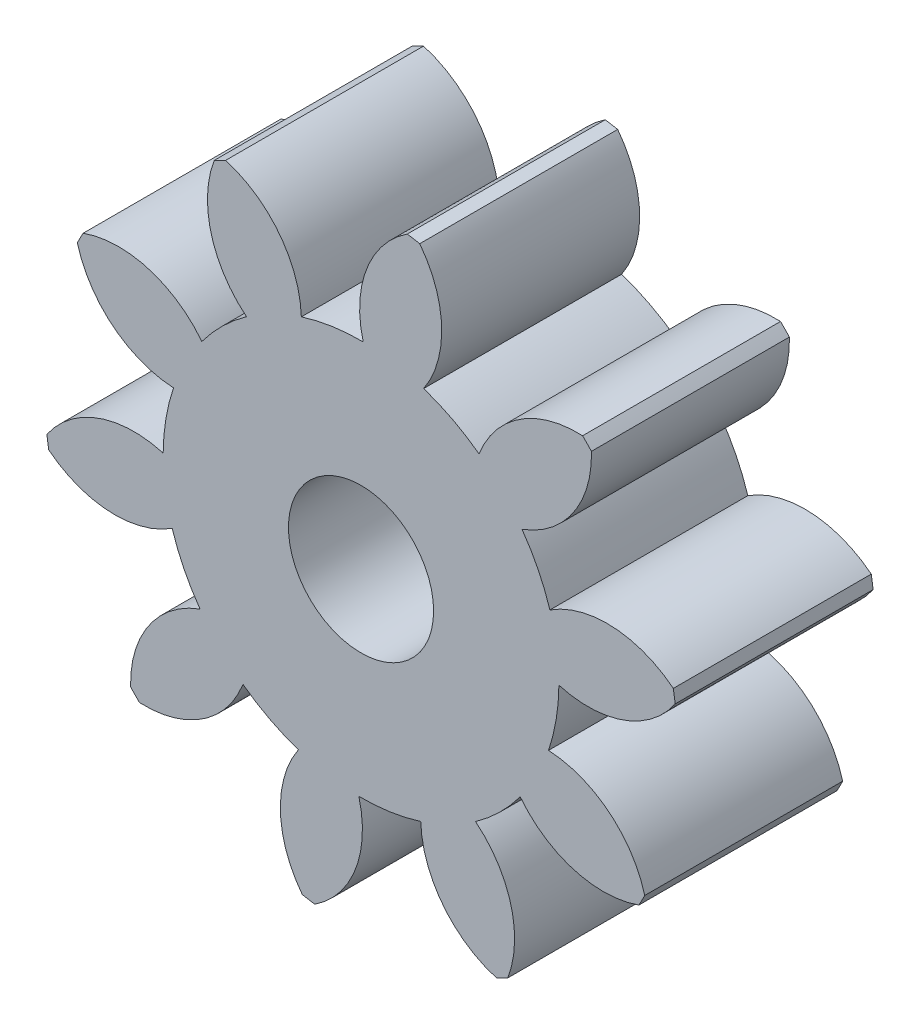
SolidWorks part; units mm, degrees
ref_plane "Front" through (0, 0, 0) normal (0, 0, 1) x (1, 0, 0)
ref_plane "Top" through (0, 0, 0) normal (0, 1, 0) x (1, 0, 0)
ref_plane "Right" through (0, 0, 0) normal (1, 0, 0) x (0, 0, -1)
sketch "Sketch1" plane through (0, 0, 0) normal (0, 0, 1) x (1, 0, 0)
  circle A0 centre (0, 0) radius 1.1
  circle A1 centre (0, 0) radius 6
  dimension "D1" = 2.2
  dimension "D2" = 12
extrude "Boss-Extrude1" add sketch "Sketch1" along normal mid plane 5.8
sketch "Sketch2" plane through (0, 0, 2.9) normal (0, 0, 1) x (1, 0, 0)
  circle A0 centre (0, 0) radius 6 construction
  circle A1 centre (0, 0) radius 6
  arc A82 (-0.9043, 2.8594) -> (-2.0525, 4.339) centre (-2.5033, 2.8039) ccw
  arc A83 (-2.0525, 4.339) -> (-2.2243, 4.2535) centre (0, 0) ccw
  arc A84 (-2.2243, 4.2535) -> (-1.7361, 2.4454) centre (-0.7277, 3.6877) ccw
  arc A85 (-1.7361, 2.4454) -> (-2.4123, 1.7818) centre (0, 0) ccw
  arc A86 (-2.4123, 1.7818) -> (-4.2109, 2.3039) centre (-3.6733, 0.7969) ccw
  arc A87 (-4.2109, 2.3039) -> (-4.2997, 2.1337) centre (0, 0) ccw
  arc A88 (-4.2997, 2.1337) -> (-2.8419, 0.9579) centre (-2.7563, 2.5556) ccw
  arc A89 (-2.8419, 0.9579) -> (-2.9989, 0.0236) centre (0, 0) ccw
  arc A90 (-2.9989, 0.0236) -> (-4.7609, -0.6112) centre (-3.4402, -1.5144) ccw
  arc A91 (-4.7609, -0.6112) -> (-4.7327, -0.801) centre (0, 0) ccw
  arc A92 (-4.7327, -0.801) -> (-2.8622, -0.8955) centre (-3.732, 0.4474) ccw
  arc A93 (-2.8622, -0.8955) -> (-2.44, -1.7437) centre (0, 0) ccw
  arc A94 (-2.44, -1.7437) -> (-3.4924, -3.2929) centre (-1.8931, -3.2473) ccw
  arc A95 (-3.4924, -3.2929) -> (-3.358, -3.4299) centre (0, 0) ccw
  arc A96 (-3.358, -3.4299) -> (-1.7892, -2.4068) centre (-3.2823, -1.8317) ccw
  arc A97 (-1.7892, -2.4068) -> (-0.9491, -2.8448) centre (0, 0) ccw
  arc A98 (-0.9491, -2.8448) -> (-0.8899, -4.7168) centre (0.3772, -3.7398) ccw
  arc A99 (-0.8899, -4.7168) -> (-0.7006, -4.7486) centre (0, 0) ccw
  arc A100 (-0.7006, -4.7486) -> (-0.0328, -2.9988) centre (-1.5788, -3.4111) ccw
  arc A101 (-0.0328, -2.9988) -> (0.9043, -2.8594) centre (0, 0) ccw
  arc A102 (0.9043, -2.8594) -> (2.0525, -4.339) centre (2.5033, -2.8039) ccw
  arc A103 (2.0525, -4.339) -> (2.2243, -4.2535) centre (0, 0) ccw
  arc A104 (2.2243, -4.2535) -> (1.7361, -2.4454) centre (0.7277, -3.6877) ccw
  arc A105 (1.7361, -2.4454) -> (2.4123, -1.7818) centre (0, 0) ccw
  arc A106 (2.4123, -1.7818) -> (4.2109, -2.3039) centre (3.6733, -0.7969) ccw
  arc A107 (4.2109, -2.3039) -> (4.2997, -2.1337) centre (0, 0) ccw
  arc A108 (4.2997, -2.1337) -> (2.8419, -0.9579) centre (2.7563, -2.5556) ccw
  arc A109 (2.8419, -0.9579) -> (2.9989, -0.0236) centre (0, 0) ccw
  arc A110 (2.9989, -0.0236) -> (4.7609, 0.6112) centre (3.4402, 1.5144) ccw
  arc A111 (4.7609, 0.6112) -> (4.7327, 0.801) centre (0, 0) ccw
  arc A112 (4.7327, 0.801) -> (2.8622, 0.8955) centre (3.732, -0.4474) ccw
  arc A113 (2.8622, 0.8955) -> (2.44, 1.7437) centre (0, 0) ccw
  arc A114 (2.44, 1.7437) -> (3.4924, 3.2929) centre (1.8931, 3.2473) ccw
  arc A115 (3.4924, 3.2929) -> (3.358, 3.4299) centre (0, 0) ccw
  arc A116 (3.358, 3.4299) -> (1.7892, 2.4068) centre (3.2823, 1.8317) ccw
  arc A117 (1.7892, 2.4068) -> (0.9491, 2.8448) centre (0, 0) ccw
  arc A118 (0.9491, 2.8448) -> (0.8899, 4.7168) centre (-0.3772, 3.7398) ccw
  arc A119 (0.8899, 4.7168) -> (0.7006, 4.7486) centre (0, 0) ccw
  arc A120 (0.7006, 4.7486) -> (0.0328, 2.9988) centre (1.5788, 3.4111) ccw
  arc A121 (0.0328, 2.9988) -> (-0.9043, 2.8594) centre (0, 0) ccw
extrude "Cut-Extrude1" cut sketch "Sketch2" against normal through all
sketch "Sketch3" plane through (0, 0, 2.9) normal (0, 0, 1) x (1, 0, 0)
  arc A40 (0.7006, 4.7486) -> (0.0328, 2.9988) centre (1.5788, 3.4111) ccw
  arc A41 (0.0328, 2.9988) -> (-0.9043, 2.8594) centre (0, 0) ccw
  arc A42 (-0.9043, 2.8594) -> (-2.0525, 4.339) centre (-2.5033, 2.8039) ccw
  arc A43 (-2.0525, 4.339) -> (-2.2243, 4.2535) centre (0, 0) ccw
  arc A44 (-2.2243, 4.2535) -> (-1.7361, 2.4454) centre (-0.7277, 3.6877) ccw
  arc A45 (-1.7361, 2.4454) -> (-2.4123, 1.7818) centre (0, 0) ccw
  arc A46 (-2.4123, 1.7818) -> (-4.2109, 2.3039) centre (-3.6733, 0.7969) ccw
  arc A47 (-4.2109, 2.3039) -> (-4.2997, 2.1337) centre (0, 0) ccw
  arc A48 (-4.2997, 2.1337) -> (-2.8419, 0.9579) centre (-2.7563, 2.5556) ccw
  arc A49 (-2.8419, 0.9579) -> (-2.9989, 0.0236) centre (0, 0) ccw
  arc A50 (-2.9989, 0.0236) -> (-4.7609, -0.6112) centre (-3.4402, -1.5144) ccw
  arc A51 (-4.7609, -0.6112) -> (-4.7327, -0.801) centre (0, 0) ccw
  arc A52 (-4.7327, -0.801) -> (-2.8622, -0.8955) centre (-3.732, 0.4474) ccw
  arc A53 (-2.8622, -0.8955) -> (-2.44, -1.7437) centre (0, 0) ccw
  arc A54 (-2.44, -1.7437) -> (-3.4924, -3.2929) centre (-1.8931, -3.2473) ccw
  arc A55 (-3.4924, -3.2929) -> (-3.358, -3.4299) centre (0, 0) ccw
  arc A56 (-3.358, -3.4299) -> (-1.7892, -2.4068) centre (-3.2823, -1.8317) ccw
  arc A57 (-1.7892, -2.4068) -> (-0.9491, -2.8448) centre (0, 0) ccw
  arc A58 (-0.9491, -2.8448) -> (-0.8899, -4.7168) centre (0.3772, -3.7398) ccw
  arc A59 (-0.8899, -4.7168) -> (-0.7006, -4.7486) centre (0, 0) ccw
  arc A60 (-0.7006, -4.7486) -> (-0.0328, -2.9988) centre (-1.5788, -3.4111) ccw
  arc A61 (-0.0328, -2.9988) -> (0.9043, -2.8594) centre (0, 0) ccw
  arc A62 (0.9043, -2.8594) -> (2.0525, -4.339) centre (2.5033, -2.8039) ccw
  arc A63 (2.0525, -4.339) -> (2.2243, -4.2535) centre (0, 0) ccw
  arc A64 (2.2243, -4.2535) -> (1.7361, -2.4454) centre (0.7277, -3.6877) ccw
  arc A65 (1.7361, -2.4454) -> (2.4123, -1.7818) centre (0, 0) ccw
  arc A66 (2.4123, -1.7818) -> (4.2109, -2.3039) centre (3.6733, -0.7969) ccw
  arc A67 (4.2109, -2.3039) -> (4.2997, -2.1337) centre (0, 0) ccw
  arc A68 (4.2997, -2.1337) -> (2.8419, -0.9579) centre (2.7563, -2.5556) ccw
  arc A69 (2.8419, -0.9579) -> (2.9989, -0.0236) centre (0, 0) ccw
  arc A70 (2.9989, -0.0236) -> (4.7609, 0.6112) centre (3.4402, 1.5144) ccw
  arc A71 (4.7609, 0.6112) -> (4.7327, 0.801) centre (0, 0) ccw
  arc A72 (4.7327, 0.801) -> (2.8622, 0.8955) centre (3.732, -0.4474) ccw
  arc A73 (2.8622, 0.8955) -> (2.44, 1.7437) centre (0, 0) ccw
  arc A74 (2.44, 1.7437) -> (3.4924, 3.2929) centre (1.8931, 3.2473) ccw
  arc A75 (3.4924, 3.2929) -> (3.358, 3.4299) centre (0, 0) ccw
  arc A76 (3.358, 3.4299) -> (1.7892, 2.4068) centre (3.2823, 1.8317) ccw
  arc A77 (1.7892, 2.4068) -> (0.9491, 2.8448) centre (0, 0) ccw
  arc A78 (0.9491, 2.8448) -> (0.8899, 4.7168) centre (-0.3772, 3.7398) ccw
  arc A79 (0.8899, 4.7168) -> (0.7006, 4.7486) centre (0, 0) ccw
  arc A80 (0.7006, 4.7486) -> (0.0328, 2.9988) centre (1.5788, 3.4111) ccw
  arc A81 (0.0328, 2.9988) -> (-0.9043, 2.8594) centre (0, 0) ccw
  arc A82 (-0.9043, 2.8594) -> (-2.0525, 4.339) centre (-2.5033, 2.8039) ccw
  arc A83 (-2.0525, 4.339) -> (-2.2243, 4.2535) centre (0, 0) ccw
  arc A84 (-2.2243, 4.2535) -> (-1.7361, 2.4454) centre (-0.7277, 3.6877) ccw
  arc A85 (-1.7361, 2.4454) -> (-2.4123, 1.7818) centre (0, 0) ccw
  arc A86 (-2.4123, 1.7818) -> (-4.2109, 2.3039) centre (-3.6733, 0.7969) ccw
  arc A87 (-4.2109, 2.3039) -> (-4.2997, 2.1337) centre (0, 0) ccw
  arc A88 (-4.2997, 2.1337) -> (-2.8419, 0.9579) centre (-2.7563, 2.5556) ccw
  arc A89 (-2.8419, 0.9579) -> (-2.9989, 0.0236) centre (0, 0) ccw
  arc A90 (-2.9989, 0.0236) -> (-4.7609, -0.6112) centre (-3.4402, -1.5144) ccw
  arc A91 (-4.7609, -0.6112) -> (-4.7327, -0.801) centre (0, 0) ccw
  arc A92 (-4.7327, -0.801) -> (-2.8622, -0.8955) centre (-3.732, 0.4474) ccw
  arc A93 (-2.8622, -0.8955) -> (-2.44, -1.7437) centre (0, 0) ccw
  arc A94 (-2.44, -1.7437) -> (-3.4924, -3.2929) centre (-1.8931, -3.2473) ccw
  arc A95 (-3.4924, -3.2929) -> (-3.358, -3.4299) centre (0, 0) ccw
  arc A96 (-3.358, -3.4299) -> (-1.7892, -2.4068) centre (-3.2823, -1.8317) ccw
  arc A97 (-1.7892, -2.4068) -> (-0.9491, -2.8448) centre (0, 0) ccw
  arc A98 (-0.9491, -2.8448) -> (-0.8899, -4.7168) centre (0.3772, -3.7398) ccw
  arc A99 (-0.8899, -4.7168) -> (-0.7006, -4.7486) centre (0, 0) ccw
  arc A100 (-0.7006, -4.7486) -> (-0.0328, -2.9988) centre (-1.5788, -3.4111) ccw
  arc A101 (-0.0328, -2.9988) -> (0.9043, -2.8594) centre (0, 0) ccw
  arc A102 (0.9043, -2.8594) -> (2.0525, -4.339) centre (2.5033, -2.8039) ccw
  arc A103 (2.0525, -4.339) -> (2.2243, -4.2535) centre (0, 0) ccw
  arc A104 (2.2243, -4.2535) -> (1.7361, -2.4454) centre (0.7277, -3.6877) ccw
  arc A105 (1.7361, -2.4454) -> (2.4123, -1.7818) centre (0, 0) ccw
  arc A106 (2.4123, -1.7818) -> (4.2109, -2.3039) centre (3.6733, -0.7969) ccw
  arc A107 (4.2109, -2.3039) -> (4.2997, -2.1337) centre (0, 0) ccw
  arc A108 (4.2997, -2.1337) -> (2.8419, -0.9579) centre (2.7563, -2.5556) ccw
  arc A109 (2.8419, -0.9579) -> (2.9989, -0.0236) centre (0, 0) ccw
  arc A110 (2.9989, -0.0236) -> (4.7609, 0.6112) centre (3.4402, 1.5144) ccw
  arc A111 (4.7609, 0.6112) -> (4.7327, 0.801) centre (0, 0) ccw
  arc A112 (4.7327, 0.801) -> (2.8622, 0.8955) centre (3.732, -0.4474) ccw
  arc A113 (2.8622, 0.8955) -> (2.44, 1.7437) centre (0, 0) ccw
  arc A114 (2.44, 1.7437) -> (3.4924, 3.2929) centre (1.8931, 3.2473) ccw
  arc A115 (3.4924, 3.2929) -> (3.358, 3.4299) centre (0, 0) ccw
  arc A116 (3.358, 3.4299) -> (1.7892, 2.4068) centre (3.2823, 1.8317) ccw
  arc A117 (1.7892, 2.4068) -> (0.9491, 2.8448) centre (0, 0) ccw
  arc A118 (0.9491, 2.8448) -> (0.8899, 4.7168) centre (-0.3772, 3.7398) ccw
  arc A119 (0.8899, 4.7168) -> (0.7006, 4.7486) centre (0, 0) ccw
  dimension "D1" = 0
extrude "Cut-Extrude2" cut sketch "Sketch3" against normal offset from surface (2.8 mm away) 3 up to face at (1.1, 0, -2.9)
